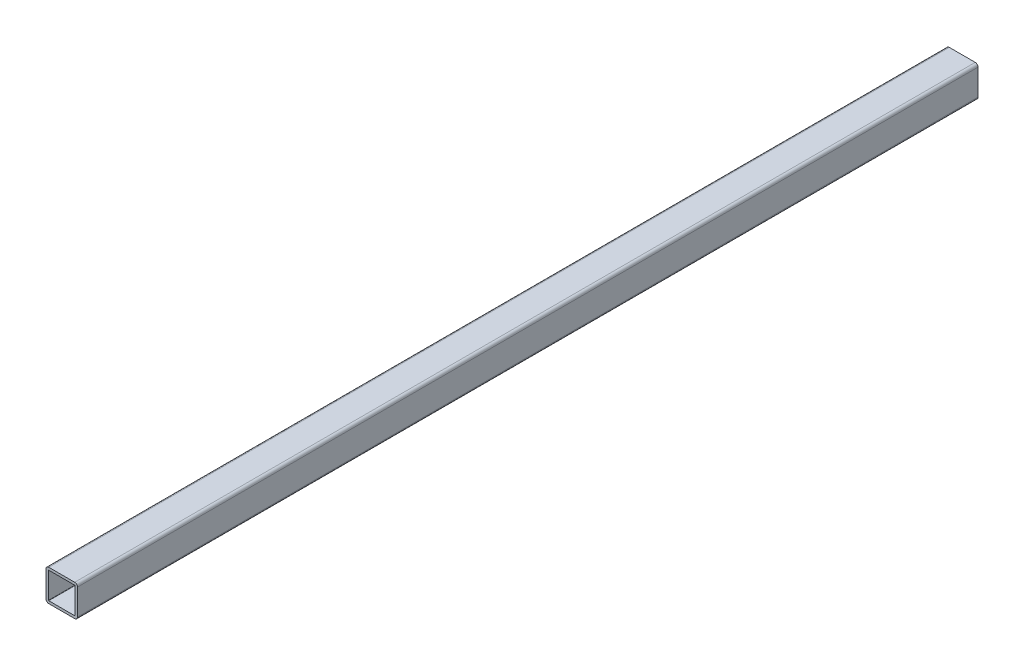
SolidWorks part; units mm, degrees
material "AISI 1020 Steel, Cold Rolled"
ref_plane "Front Plane" through (0, 0, 0) normal (0, 0, 1) x (1, 0, 0)
ref_plane "Top Plane" through (0, 0, 0) normal (0, 1, 0) x (1, 0, 0)
ref_plane "Right Plane" through (0, 0, 0) normal (1, 0, 0) x (0, 0, -1)
sketch "Sketch1" plane through (0, 0, 0) normal (0, 1, 0) x (1, 0, 0)
  line L0 (0, 0) -> (0, 715)
  dimension "D1" = 715
other "Structural Member1"
ref_plane "Plane1" through (0, 0, 0) normal (0, 0, -1) x (-1, 0, 0)
sketch "Sketch11" plane through (0, 0, 0) normal (0, 0, -1) x (-1, 0, 0)
  line L0 (-10.3, -10.5) -> (10.3, -10.5)
  line L1 (-10.5, -10.3) -> (-10.5, 10.3)
  line L2 (10.3, 10.5) -> (-10.3, 10.5)
  line L3 (10.5, 10.3) -> (10.5, -10.3)
  line L4 (-10.3, -12.5) -> (10.3, -12.5)
  line L5 (-12.5, -10.3) -> (-12.5, 10.3)
  line L6 (10.3, 12.5) -> (-10.3, 12.5)
  line L7 (12.5, 10.3) -> (12.5, -10.3)
  arc A0 (12.5, 10.3) -> (10.3, 12.5) centre (10.3, 10.3) ccw
  arc A1 (10.3, -12.5) -> (12.5, -10.3) centre (10.3, -10.3) ccw
  arc A2 (-12.5, -10.3) -> (-10.3, -12.5) centre (-10.3, -10.3) ccw
  arc A3 (-10.3, 12.5) -> (-12.5, 10.3) centre (-10.3, 10.3) ccw
  arc A4 (-10.3, 10.5) -> (-10.5, 10.3) centre (-10.3, 10.3) ccw
  arc A5 (10.5, 10.3) -> (10.3, 10.5) centre (10.3, 10.3) ccw
  arc A6 (10.3, -10.5) -> (10.5, -10.3) centre (10.3, -10.3) ccw
  arc A7 (-10.5, -10.3) -> (-10.3, -10.5) centre (-10.3, -10.3) ccw
  point P0 (-12.5, 0)
  point P1 (12.5, 0)
  point P2 (0, 12.5)
  point P3 (0, -12.5)
  point P4 (0, 0)
  point P5 (-12.5, -12.5)
  point P6 (12.5, -12.5)
  point P7 (12.5, 12.5)
  point P8 (-12.5, 12.5)
  point P33 (0, 0)
  dimension "D1" = 2.2
  dimension "Thickness" = 2
  dimension "V_leg" = 25
